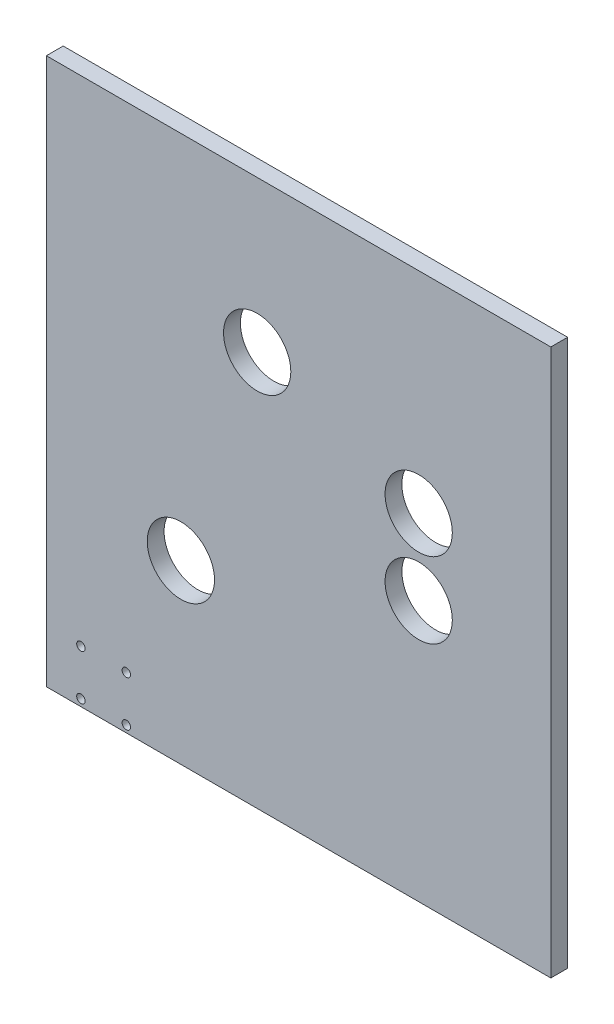
SolidWorks part; units mm, degrees
ref_plane "前视基准面" through (0, 0, 0) normal (0, 0, 1) x (1, 0, 0)
ref_plane "上视基准面" through (0, 0, 0) normal (0, 1, 0) x (1, 0, 0)
ref_plane "右视基准面" through (0, 0, 0) normal (1, 0, 0) x (0, 0, -1)
other "Configuration Table"
sketch "草图1" plane through (0, 0, 0) normal (0, 0, 1) x (1, 0, 0)
  line L1 (-150, -150) -> (150, -150)
  line L2 (-150, -150) -> (-150, 150)
  line L3 (-150, 150) -> (150, 150)
  line L4 (150, -150) -> (150, 150)
  line L5 (-150, -150) -> (150, 150) construction
  line L6 (-150, 150) -> (150, -150) construction
  point P0 (0, 0)
  dimension "D1" = 300
  dimension "D2" = 300
extrude "凸台-拉伸1" add sketch "草图1" along normal blind 10
sketch "草图2" plane through (0, 0, 10) normal (0, 0, 1) x (1, 0, 0)
  line L0 (-150, 150) -> (-150, -150) construction
  line L1 (-150, -150) -> (150, -150) construction
  line L2 (150, 150) -> (-150, 150) construction
  circle A0 centre (-70, -70) radius 20
  circle A1 centre (71.4214, -20) radius 20
  circle A2 centre (-24.6255, 60) radius 20
  circle A3 centre (71.4214, 25) radius 20
  dimension "D3" = 40
  dimension "D4" = 40
  dimension "D8" = 40
  dimension "D10" = 40
  dimension "D1" = 80
  dimension "D2" = 80
  dimension "D5" = 150
  dimension "D6" = 50
  dimension "D7" = 125
  dimension "D9" = 80
  dimension "D11" = 45
  dimension "D12" = 150
extrude "切除-拉伸1" cut sketch "草图2" against normal through all
sketch "草图5" plane through (0, -150, 0) normal (0, -1, 0) x (1, 0, 0)
  line L4 (-150, 0) -> (150, 0)
  line L5 (150, 0) -> (150, 10)
  line L6 (150, 10) -> (-150, 10)
  line L7 (-150, 10) -> (-150, 0)
  line L8 (-150, 0) -> (150, 0)
  line L9 (150, 0) -> (150, 10)
  line L10 (150, 10) -> (-150, 10)
  line L11 (-150, 10) -> (-150, 0)
  dimension "D1" = 0
extrude "凸台-拉伸2" add sketch "草图5" along normal blind 25
sketch "草图7" plane through (0, 0, 0) normal (0, 0, -1) x (-1, 0, 0)
  circle A0 centre (129.4536, -143.875) radius 2.5
  circle A1 centre (102.4536, -143.875) radius 2.5
  circle A2 centre (129.4536, -170.875) radius 2.5
  circle A3 centre (102.4536, -170.875) radius 2.5
extrude "切除-拉伸5" cut sketch "草图7" against normal through all
